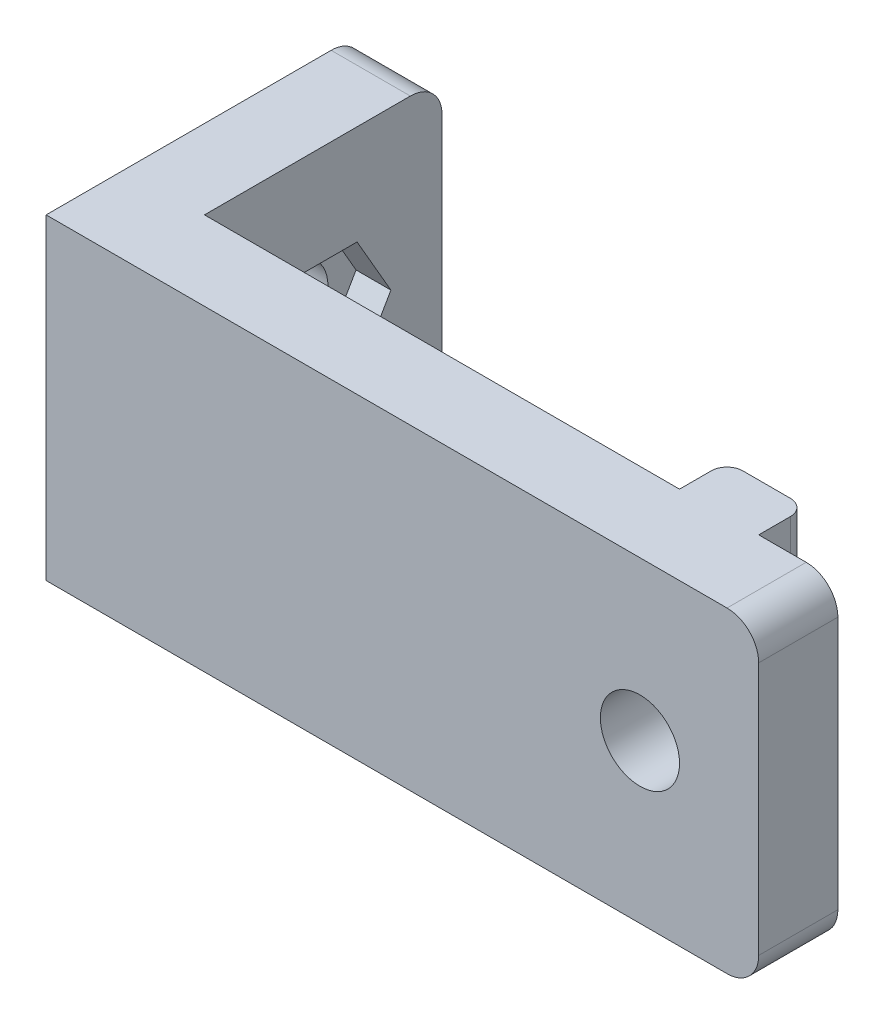
SolidWorks part; units mm, degrees
ref_plane "Front Plane" through (0, 0, 0) normal (0, 0, 1) x (1, 0, 0)
ref_plane "Top Plane" through (0, 0, 0) normal (0, 1, 0) x (1, 0, 0)
ref_plane "Right Plane" through (0, 0, 0) normal (1, 0, 0) x (0, 0, -1)
sketch "Sketch1" plane through (0, 0, 0) normal (0, 0, 1) x (1, 0, 0)
  line L1 (22.5, -10) -> (-22.5, -10)
  line L2 (22.5, -10) -> (22.5, 10)
  line L3 (22.5, 10) -> (-22.5, 10)
  line L4 (-22.5, -10) -> (-22.5, 10)
  line L5 (22.5, -10) -> (-22.5, 10) construction
  line L6 (22.5, 10) -> (-22.5, -10) construction
  point P0 (0, 0)
  dimension "D1" = 20
  dimension "D2" = 45
extrude "Boss-Extrude1" add sketch "Sketch1" along normal blind 5
sketch "Sketch2" plane through (0, 0, 0) normal (0, 0, -1) x (-1, 0, 0)
  line L0 (22.5, -10) -> (-22.5, -10) construction
  line L1 (22.5, 10) -> (17.5, 10)
  line L2 (22.5, 10) -> (22.5, -10)
  line L3 (22.5, -10) -> (17.5, -10)
  line L4 (17.5, 10) -> (17.5, -10)
  dimension "D1" = 5
extrude "Boss-Extrude2" add sketch "Sketch2" along normal blind 15
sketch "Sketch3" plane through (-17.5, 0, 0) normal (1, 0, 0) x (0, 0, -1)
  circle A0 centre (7.5, 0) radius 2.5
extrude "Cut-Extrude1" cut sketch "Sketch3" against normal blind 15
sketch "Sketch4" plane through (0, 0, 5) normal (0, 0, 1) x (1, 0, 0)
  line L0 (22.5, -10) -> (22.5, 10) construction
  circle A0 centre (15, 0) radius 2.5
  dimension "D1" = 7.5
extrude "Cut-Extrude2" cut sketch "Sketch4" against normal blind 15
sketch "Sketch5" plane through (0, 0, 0) normal (0, 0, -1) x (-1, 0, 0)
  line L0 (-22.5, 10) -> (17.5, 10) construction
  line L1 (-17.5, 10) -> (-12.5, 10)
  line L2 (-17.5, 10) -> (-17.5, 6)
  line L3 (-17.5, 6) -> (-12.5, 6)
  line L4 (-12.5, 10) -> (-12.5, 6)
  line L5 (55, 0) -> (-55, 0) construction
  line L6 (-12.5, -10) -> (-12.5, -6)
  line L7 (-17.5, -6) -> (-12.5, -6)
  line L8 (-17.5, -10) -> (-17.5, -6)
  line L9 (-17.5, -10) -> (-12.5, -10)
  circle A0 centre (-15, 0) radius 2.5 construction
  point P6 (-15, 6)
  dimension "D1" = 4
  dimension "D2" = 5
  dimension "D3" = 0
extrude "Boss-Extrude3" add sketch "Sketch5" along normal blind 3
fillet "Fillet1" radius 1 4 edges at (12.5, -8, -3) (17.5, -8, -3) (12.5, 8, -3) (17.5, 8, -3)
fillet "Fillet2" radius 2 4 edges at (-20, 10, -15) (-20, -10, -15) (22.5, 10, 2.5) (22.5, -10, 2.5)
sketch "Sketch6" plane through (-17.5, 0, 0) normal (1, 0, 0) x (0, 0, -1)
  line L1 (3.2276, 0) -> (5.3638, -3.7)
  line L2 (5.3638, -3.7) -> (9.6362, -3.7)
  line L3 (9.6362, -3.7) -> (11.7724, 0)
  line L4 (11.7724, 0) -> (9.6362, 3.7)
  line L5 (9.6362, 3.7) -> (5.3638, 3.7)
  line L6 (5.3638, 3.7) -> (3.2276, 0)
  circle A0 centre (7.5, 0) radius 3.7 construction
  dimension "D1" = 7.4
extrude "Cut-Extrude3" cut sketch "Sketch6" against normal blind 2.2
